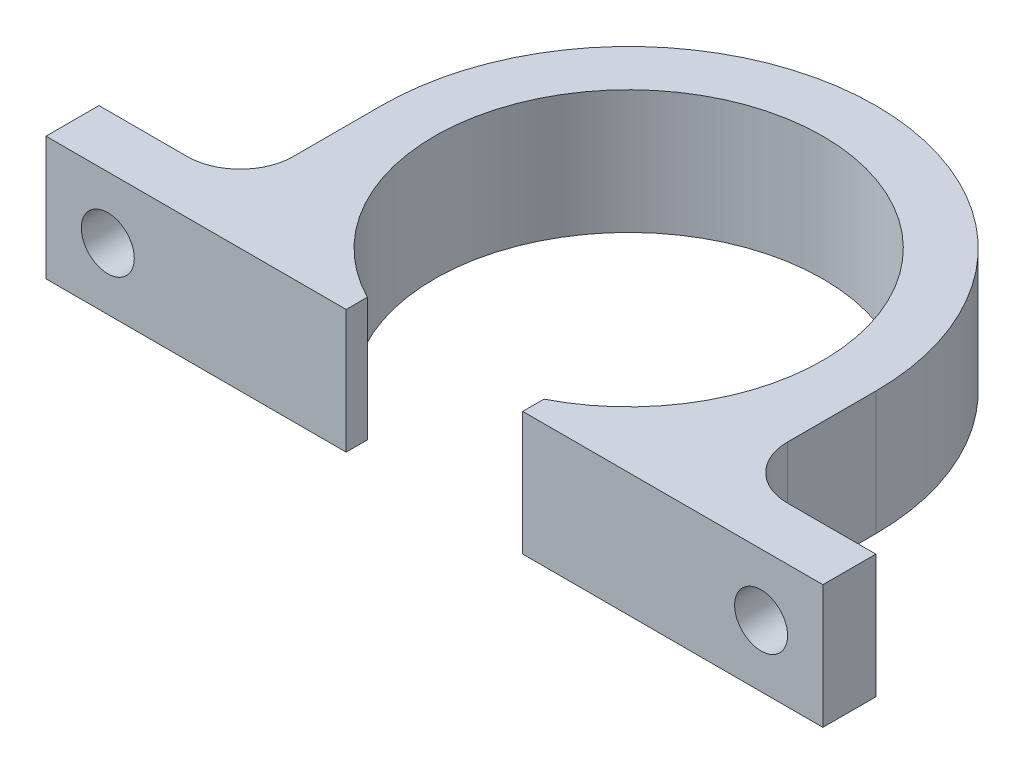
SolidWorks part; units mm, degrees
ref_plane "Front Plane" through (0, 0, 0) normal (0, 0, 1) x (1, 0, 0)
ref_plane "Top Plane" through (0, 0, 0) normal (0, 1, 0) x (1, 0, 0)
ref_plane "Right Plane" through (0, 0, 0) normal (1, 0, 0) x (0, 0, -1)
sketch "Sketch1" plane through (0, 0, 0) normal (0, 1, 0) x (1, 0, 0)
  line L1 (22, -11) -> (0, -11)
  line L2 (22, -11) -> (22, -8)
  line L3 (22, -8) -> (0, -8)
  line L4 (0, -11) -> (0, -8)
  line L5 (-22, -11) -> (0, -11)
  line L6 (-22, -11) -> (-22, -8)
  line L7 (-22, -8) -> (0, -8)
  line L8 (0, -11) -> (0, -8)
  line L9 (-14, 0) -> (14, 0)
  line L10 (-14, 0) -> (-14, -11)
  line L11 (-14, -11) -> (14, -11)
  line L12 (14, 0) -> (14, -11)
  line L13 (0, -11) -> (-5, -11)
  line L14 (0, -11) -> (0, -8)
  line L15 (0, -8) -> (-5, -8)
  line L16 (-5, -11) -> (-5, -8)
  line L17 (0, -11) -> (5, -11)
  line L18 (0, -11) -> (0, -8)
  line L19 (0, -8) -> (5, -8)
  line L20 (5, -11) -> (5, -8)
  circle A0 centre (0, 0) radius 11
  circle A1 centre (0, 0) radius 14
  dimension "D1" = 22
  dimension "D2" = 28
  dimension "D3" = 3
  dimension "D4" = 22
  dimension "D5" = 22
  dimension "D6" = 8
  dimension "D7" = 8
  dimension "D8" = 8
  dimension "D9" = 5
  dimension "D10" = 5
extrude "Boss-Extrude2" add sketch "Sketch1" along normal blind 7 contours L10 L7 L6 L5 | A1 L10 L7 | A1 L7 L10 L5 | L7 A1 L11 L16 A0 | L9 A1 L7 A0 | L9 A1 A0 | L3 A1 L9 A0 | L11 A1 L3 A0 L20 | A1 L3 L12 | A1 L1 L12 L3 | L3 L12 L1 L2
fillet "Fillet3" radius 3 1 edges at (14, 3.5, 8)
fillet "Fillet4" radius 3 1 edges at (-14, 3.5, 8)
sketch "Sketch3" plane through (0, 0, 11) normal (0, 0, 1) x (1, 0, 0)
  line L0 (-22, 7) -> (-5, 7) construction
  line L2 (-22, 7) -> (-22, 0) construction
  line L3 (22, 7) -> (5, 7) construction
  line L4 (22, 7) -> (22, 0) construction
  circle A0 centre (-18.5, 3.5) radius 1.5
  circle A1 centre (18.5, 3.5) radius 1.5
  point P8 (-22, 3.5)
  point P13 (22, 3.5)
  dimension "D1" = 3
  dimension "D4" = 3
  dimension "D2" = 3.5
  dimension "D3" = 3.5
  dimension "D5" = 3.5
  dimension "D6" = 3.5
extrude "Cut-Extrude1" cut sketch "Sketch3" against normal blind 7
